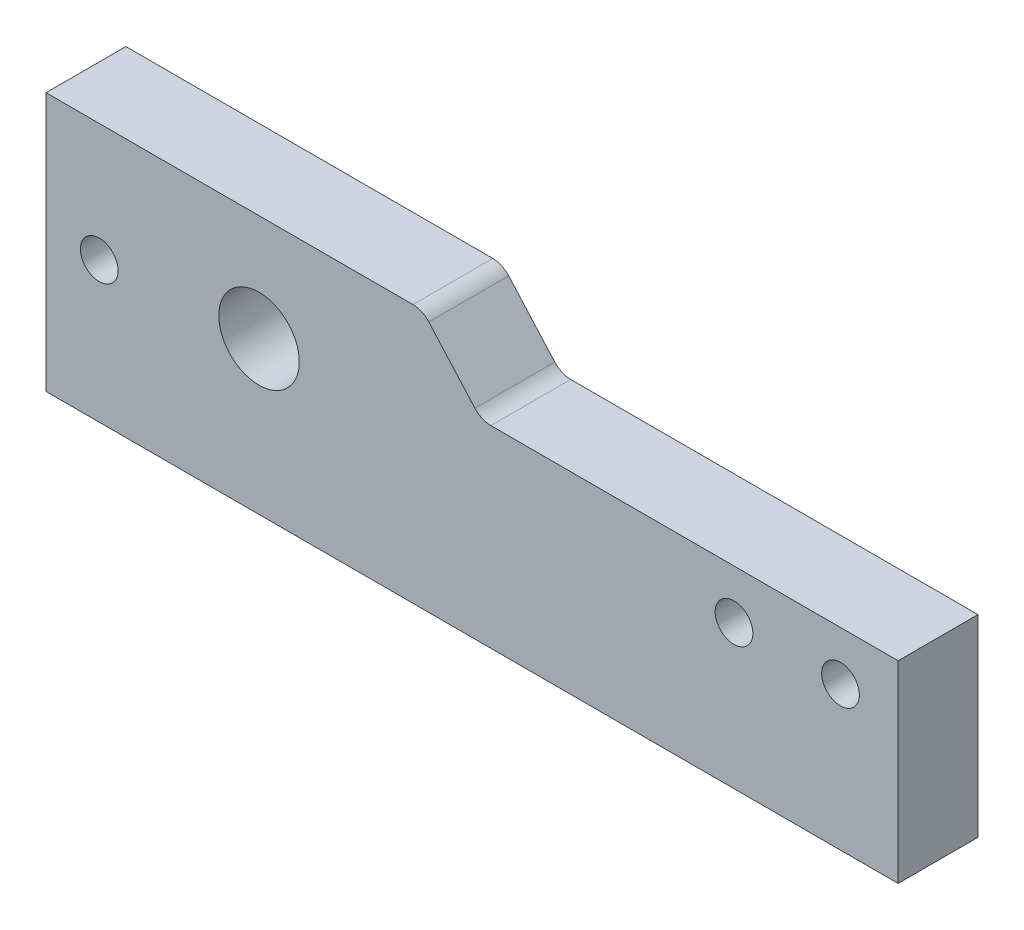
SolidWorks part; units mm, degrees
ref_plane "Front Plane" through (0, 0, 0) normal (0, 0, 1) x (1, 0, 0)
ref_plane "Top Plane" through (0, 0, 0) normal (0, 1, 0) x (1, 0, 0)
ref_plane "Right Plane" through (0, 0, 0) normal (1, 0, 0) x (0, 0, -1)
sketch "Sketch1" plane through (0, 0, 0) normal (0, 0, 1) x (1, 0, 0)
  line L1 (50.8, -22.225) -> (-50.8, -22.225)
  line L2 (50.8, -22.225) -> (50.8, 22.225)
  line L3 (50.8, 22.225) -> (-50.8, 22.225)
  line L4 (-50.8, -22.225) -> (-50.8, 22.225)
  line L5 (50.8, -22.225) -> (-50.8, 22.225) construction
  line L6 (50.8, 22.225) -> (-50.8, -22.225) construction
  point P0 (0, 0)
  dimension "D1" = 101.6
  dimension "D2" = 44.45
extrude "Boss-Extrude1" add sketch "Sketch1" along normal blind 9.525
sketch "Sketch3" plane through (0, 0, 9.525) normal (0, 0, 1) x (1, 0, 0)
  line L0 (-48.998, 18.1039) -> (-27.202, -13.0239) construction
  line L1 (50.8, 22.225) -> (-50.8, 22.225) construction
  circle A0 centre (-38.1, 2.54) radius 19 construction
  point P8 (-48.998, 18.1039)
  point P9 (-27.202, -13.0239)
  dimension "D1" = 38
  dimension "D2" = 38.1
  dimension "D3" = 2.54
  dimension "D4" = 55
hole_wizard "Tap Drill for #8-32 Tap1" positions "Sketch3" profile "Sketch5" hole size "#8-32" standard "ANSI Inch"
sketch "Sketch5" plane through (-27.202, -13.0239, 6.35) normal (1, 0, 0) x (0, -1, 0)
  line L0 (0, 0) -> (0, 6.35)
  line L1 (0, 6.35) -> (1.7272, 6.35)
  line L2 (1.7272, 6.35) -> (1.7272, 0)
  line L5 (1.7272, 0) -> (0, 0)
  line L11 (0, -6.35) -> (0, 107.95) construction
  dimension "Thru Hole Dia." = 3.4544
  dimension "Thru Hole Depth" = 6.35
sketch "Sketch6" plane through (0, 0, 0) normal (0, 0, 1) x (1, 0, 0)
  line L0 (-27.4142, 13.549) -> (-23.3858, 5.501) construction
  line L1 (50.8, 22.225) -> (-50.8, 22.225) construction
  line L2 (-50.8, 22.225) -> (-50.8, -22.225) construction
  circle A0 centre (-25.4, 9.525) radius 4.5 construction
  circle A1 centre (-25.4, 9.525) radius 4.8
  point P8 (-27.4142, 13.549)
  point P9 (-23.3858, 5.501)
  dimension "D1" = 9
  dimension "D2" = 12.7
  dimension "D3" = 9.6
  dimension "D4" = 25.4
extrude "Cut-Extrude1" cut sketch "Sketch6" along normal through all contours A1
sketch "Sketch10" plane through (0, 0, 9.525) normal (0, 0, 1) x (1, 0, 0)
  circle A0 centre (-46.1155, -16.764) radius 2.286
  circle A1 centre (-25.4, 9.525) radius 4.8 construction
  dimension "D1" = 4.572
  dimension "D2" = 26.289
extrude "Cut-Extrude2" cut sketch "Sketch10" against normal blind 3.81
sketch "Sketch11" plane through (0, 0, 0) normal (0, 0, -1) x (-1, 0, 0)
  circle A0 centre (-43.9318, 8.5185) radius 2.2479 construction
  circle A1 centre (-31.2318, 8.5185) radius 2.2479 construction
  point P0 (-43.9318, 8.5185)
  point P3 (-31.2318, 8.5185)
hole_wizard "#8 Clearance Hole1" positions "Sketch11" profile "Sketch12" hole size "#8" standard "ANSI Inch" end condition through all
sketch "Sketch12" plane through (43.9318, 8.5185, 0) normal (1, 0, 0) x (0, 1, 0)
  line L0 (0, 0) -> (0, 9.525)
  line L1 (0, 9.525) -> (2.2479, 9.525)
  line L2 (2.2479, 9.525) -> (2.2479, 0)
  line L5 (2.2479, 0) -> (0, 0)
  line L11 (0, -6.35) -> (0, 107.95) construction
  dimension "Thru Hole Dia." = 4.4958
  dimension "Thru Hole Depth" = 9.525
sketch "Sketch13" plane through (0, 0, 0) normal (0, 0, -1) x (-1, 0, 0)
  line L0 (50.8, -22.225) -> (-50.8, -22.225) construction
  line L1 (-54.8068, -8.6265) -> (54.8068, -8.6265)
  line L2 (-54.8068, -8.6265) -> (-54.8068, -35.8235)
  line L3 (-54.8068, -35.8235) -> (54.8068, -35.8235)
  line L4 (54.8068, -8.6265) -> (54.8068, -35.8235)
  line L5 (-54.8068, -8.6265) -> (54.8068, -35.8235) construction
  line L6 (-54.8068, -35.8235) -> (54.8068, -8.6265) construction
  point P0 (0, -22.225)
extrude "Cut-Extrude3" cut sketch "Sketch13" against normal through all
sketch "Sketch14" plane through (0, 0, 0) normal (0, 0, -1) x (-1, 0, 0)
  line L0 (-50.8, 14.3689) -> (-1.0961, 14.3689)
  line L1 (6.4513, 22.8295) -> (-0.3386, 15.218)
  line L2 (10.8191, 27.7258) -> (-0.3386, 15.218) construction
  line L3 (-0.3386, 15.218) -> (-1.0961, 14.3689)
  line L4 (6.4513, 22.8295) -> (6.4513, 26.3693)
  line L5 (6.4513, 26.3693) -> (-61.1176, 26.3693)
  line L6 (-61.1176, 26.3693) -> (-61.1176, 13.2924)
  line L7 (-61.1176, 13.2924) -> (-50.8, 14.3689)
extrude "Cut-Extrude5" cut sketch "Sketch14" against normal through all
fillet "Fillet1" radius 2.54 2 edges at (-5.9121, 22.225, 4.7625) (1.0961, 14.3689, 4.7625)
sketch "Sketch15" plane through (0, 0, 0) normal (0, 0, -1) x (-1, 0, 0)
  circle A0 centre (44.45, 8.14) radius 2.2479
extrude "Cut-Extrude6" cut sketch "Sketch15" against normal through all
